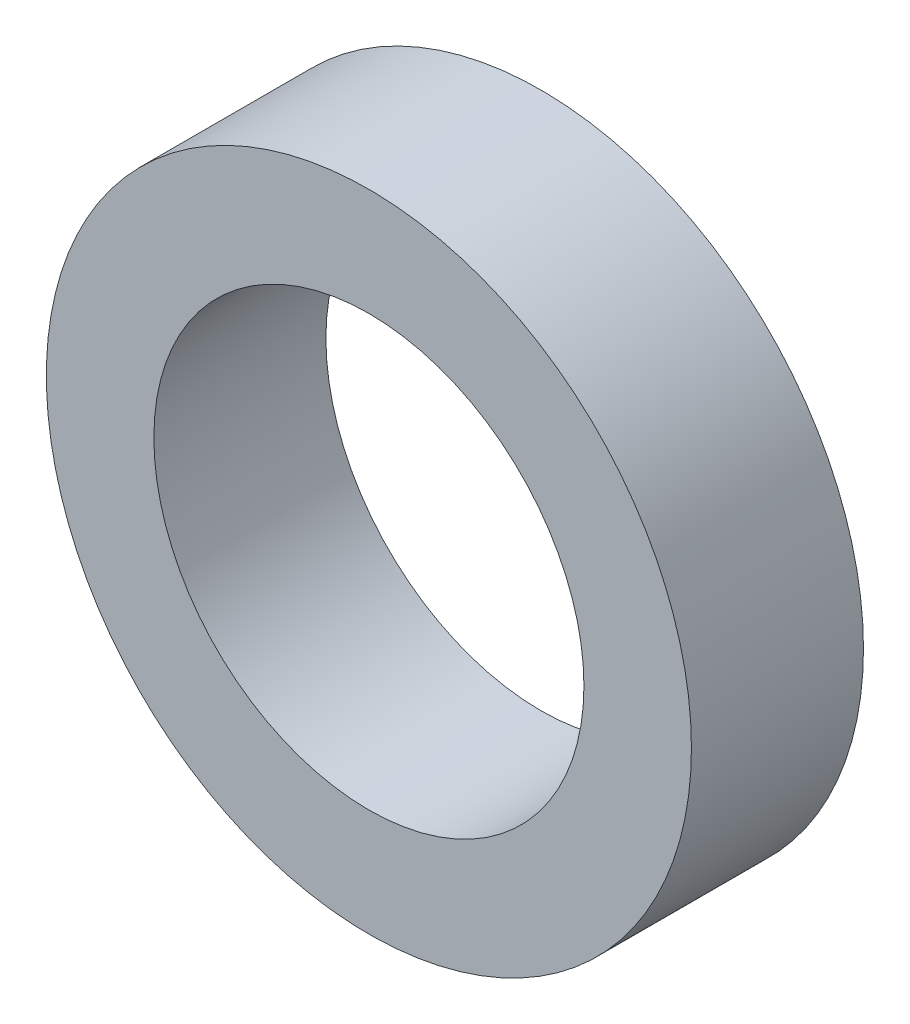
SolidWorks part; units mm, degrees
ref_plane "前视基准面" through (0, 0, 0) normal (0, 0, 1) x (1, 0, 0)
ref_plane "上视基准面" through (0, 0, 0) normal (0, 1, 0) x (1, 0, 0)
ref_plane "右视基准面" through (0, 0, 0) normal (1, 0, 0) x (0, 0, -1)
sketch "草图1" plane through (0, 0, 0) normal (0, 0, 1) x (1, 0, 0)
  circle A0 centre (0, 0) radius 7.5
  circle A1 centre (0, 0) radius 5
  dimension "D1" = 15
  dimension "D2" = 10
extrude "凸台-拉伸1" add sketch "草图1" along normal blind 4
